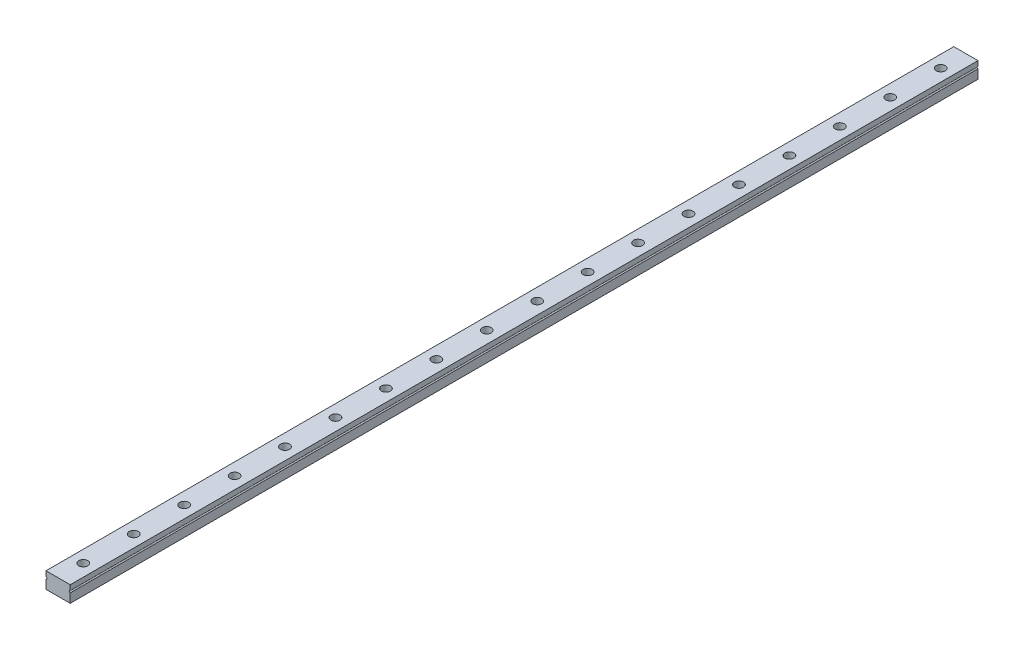
SolidWorks part; units mm, degrees
ref_plane "Front Plane" through (0, 0, 0) normal (0, 0, 1) x (1, 0, 0)
ref_plane "Top Plane" through (0, 0, 0) normal (0, 1, 0) x (1, 0, 0)
ref_plane "Right Plane" through (0, 0, 0) normal (1, 0, 0) x (0, 0, -1)
sketch "Rail-Sketch1" plane through (0, 0, 0) normal (0, 0, 1) x (1, 0, 0)
  line L0 (0, 0) -> (12, 0)
  line L1 (12, 0) -> (12, 4.5)
  line L2 (0, 4.5) -> (0, 0)
  line L3 (0, 8) -> (12, 8)
  line L4 (0, 8) -> (0, 5.5)
  line L5 (12, 8) -> (12, 5.5)
  arc A0 (0, 5.5) -> (0, 4.5) centre (0, 5) cw
  arc A1 (12, 5.5) -> (12, 4.5) centre (12, 5) ccw
  point P7 (0.5, 5)
  dimension "D1" = 12
  dimension "D2" = 8
  dimension "D5" = 11
  dimension "D3" = 2.5
extrude "Boss-Extrude1" add sketch "Rail-Sketch1" along normal blind 450
sketch "RailHoles-Sketch1" plane through (0, 8, 0) normal (0, 1, 0) x (1, 0, 0)
  line L0 (12, -450) -> (0, -450) construction
  line L3 (12, -450) -> (12, 0) construction
  circle A0 centre (6, -437.5) radius 1.75
  circle A25 centre (6, -412.5) radius 1.75
  circle A26 centre (6, -387.5) radius 1.75
  circle A27 centre (6, -362.5) radius 1.75
  circle A28 centre (6, -337.5) radius 1.75
  circle A29 centre (6, -312.5) radius 1.75
  circle A30 centre (6, -287.5) radius 1.75
  circle A31 centre (6, -262.5) radius 1.75
  circle A32 centre (6, -237.5) radius 1.75
  circle A33 centre (6, -212.5) radius 1.75
  circle A34 centre (6, -187.5) radius 1.75
  circle A35 centre (6, -162.5) radius 1.75
  circle A36 centre (6, -137.5) radius 1.75
  circle A37 centre (6, -112.5) radius 1.75
  circle A38 centre (6, -87.5) radius 1.75
  circle A39 centre (6, -62.5) radius 1.75
  circle A40 centre (6, -37.5) radius 1.75
  circle A41 centre (6, -12.5) radius 1.75
  dimension "D3" = 3.5
  dimension "D1" = 12.5
  dimension "D2" = 6
  dimension "D4" = 18
extrude "RailHoles-Cut-Extrude1" cut sketch "RailHoles-Sketch1" against normal through all
sketch "RailBoreHoles-Sketch2" plane through (0, 8, 0) normal (0, 1, 0) x (1, 0, 0)
  circle A0 centre (6, -437.5) radius 2.25
  circle A1 centre (6, -87.5) radius 2.25
  circle A2 centre (6, -412.5) radius 2.25
  circle A3 centre (6, -387.5) radius 2.25
  circle A4 centre (6, -362.5) radius 2.25
  circle A5 centre (6, -337.5) radius 2.25
  circle A6 centre (6, -312.5) radius 2.25
  circle A7 centre (6, -287.5) radius 2.25
  circle A8 centre (6, -262.5) radius 2.25
  circle A9 centre (6, -237.5) radius 2.25
  circle A10 centre (6, -212.5) radius 2.25
  circle A11 centre (6, -187.5) radius 2.25
  circle A12 centre (6, -162.5) radius 2.25
  circle A13 centre (6, -137.5) radius 2.25
  circle A14 centre (6, -112.5) radius 2.25
  circle A15 centre (6, -437.5) radius 1.75 construction
  circle A16 centre (6, -62.5) radius 2.25
  circle A17 centre (6, -37.5) radius 2.25
  circle A18 centre (6, -12.5) radius 2.25
  dimension "D1" = 4.5
  dimension "D3" = 25
  dimension "D2" = 18
extrude "RailBoreHoles-Cut-Extrude2" cut sketch "RailBoreHoles-Sketch2" against normal blind 4
equation "\"LinearRailWidth\"= 12mm'Spec"
equation "\"D1@Rail-Sketch1\" = \"LinearRailWidth\""
equation "\"LinearRailHeight\"= 8mm'Spec"
equation "\"D2@Rail-Sketch1\" = \"LinearRailHeight\""
equation "\"LinearRailLength\"= 450mm'Spec"
equation "\"D1@Boss-Extrude1\"=\"LinearRailLength\""
equation "\"LinearRailHoleOuterBore\"= 4.5mm'Spec"
equation "\"LinearRailHoleDiameter\"= 3.5mm'Spec"
equation "\"LinearRailHoleOuterBoreDepth\"= 4mm'Spec"
equation "\"LinearRailHoleDistance\"= 25mm'Spec"
equation "\"LinearRailFirstHoleOffsetFromEdge\"= 12.5mm'Spec"
equation "\"D1@RailHoles-Sketch1\" = \"LinearRailFirstHoleOffsetFromEdge\""
equation "\"D2@RailHoles-Sketch1\" = \"LinearRailWidth\" / 2"
equation "\"D3@RailHoles-Sketch1\" = \"LinearRailHoleDiameter\""
equation "\"D1@RailBoreHoles-Sketch2\" = \"LinearRailHoleOuterBore\""
equation "\"D3@RailBoreHoles-Sketch2\" = \"LinearRailHoleDistance\""
equation "\"D1@RailBoreHoles-Cut-Extrude2\"=\"LinearRailHoleOuterBoreDepth\""
